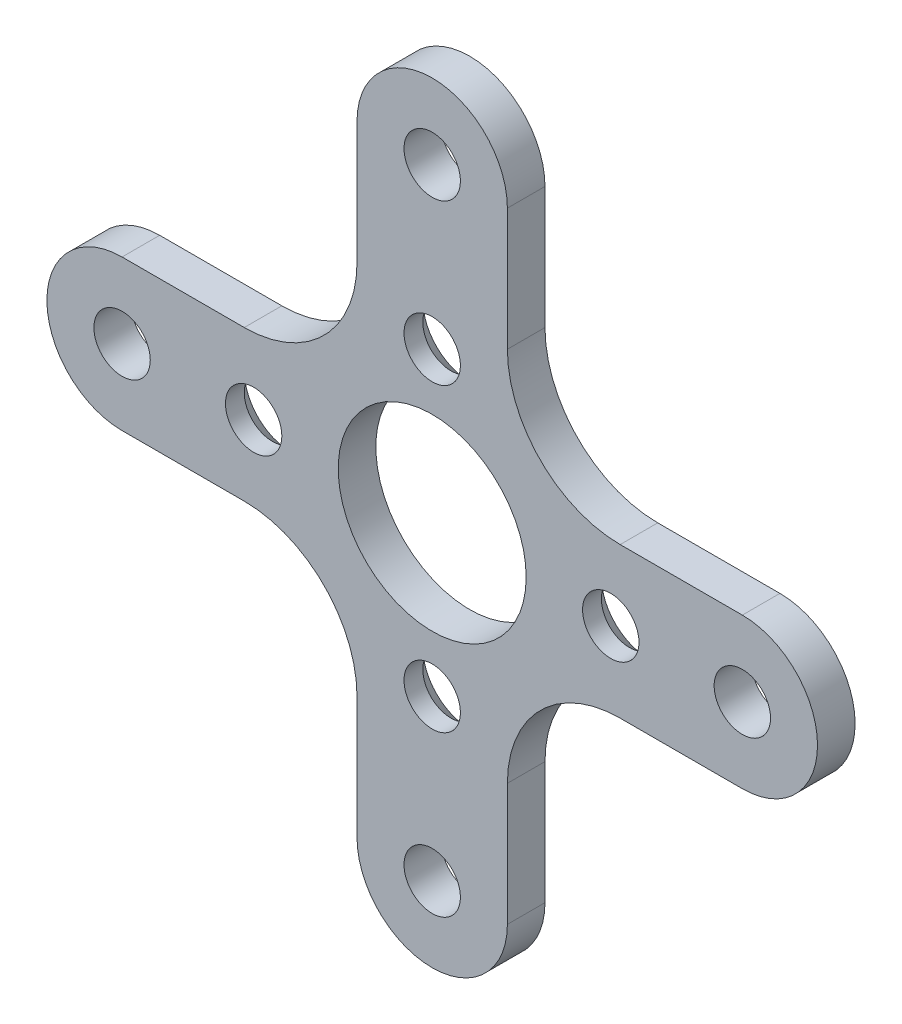
SolidWorks part; units mm, degrees
ref_plane "Ön Düzlem" through (0, 0, 0) normal (0, 0, 1) x (1, 0, 0)
ref_plane "Üst Düzlem" through (0, 0, 0) normal (0, 1, 0) x (1, 0, 0)
ref_plane "Sağ Düzlem" through (0, 0, 0) normal (1, 0, 0) x (0, 0, -1)
sketch "Çizim1" plane through (0, 0, 0) normal (0, 0, 1) x (1, 0, 0)
  line L0 (0, 0) -> (0, 16.5) construction
  line L1 (10, 4) -> (16.5, 4)
  line L2 (10, -4) -> (16.5, -4)
  line L3 (4, -10) -> (4, -16.5)
  line L4 (-4, -10) -> (-4, -16.5)
  line L5 (-10, -4) -> (-16.5, -4)
  line L6 (-10, 4) -> (-16.5, 4)
  line L7 (-4, 10) -> (-4, 16.5)
  line L9 (4, 10) -> (4, 16.5)
  circle A0 centre (0, 8) radius 1.5
  arc A1 (4, 16.5) -> (-4, 16.5) centre (0, 16.5) ccw
  arc A2 (16.5, -4) -> (16.5, 4) centre (16.5, 0) ccw
  circle A3 centre (16.5, 0) radius 1.5
  circle A4 centre (9.5, 0) radius 1.5
  arc A5 (10, -4) -> (4, -10) centre (10, -10) ccw
  arc A6 (4, 10) -> (10, 4) centre (10, 10) ccw
  arc A7 (-4, -16.5) -> (4, -16.5) centre (0, -16.5) ccw
  circle A8 centre (0, 16.5) radius 1.5
  circle A9 centre (0, -16.5) radius 1.5
  circle A10 centre (0, -8) radius 1.5
  arc A11 (-4, -10) -> (-10, -4) centre (-10, -10) ccw
  circle A12 centre (0, 0) radius 5
  arc A13 (-16.5, 4) -> (-16.5, -4) centre (-16.5, 0) ccw
  circle A14 centre (-16.5, 0) radius 1.5
  circle A15 centre (-9.5, 0) radius 1.5
  arc A16 (-10, 4) -> (-4, 10) centre (-10, 10) ccw
  point P2 (0, 0)
  point P6 (-9.5686, 0)
  point P9 (0, 0)
  point P39 (0, 0)
  point P49 (0, 0)
  dimension "D3" = 4
  dimension "D4" = 10
  dimension "D5" = 10
  dimension "D6" = 3
  dimension "D1" = 6
  dimension "D2" = 16.5
  dimension "D7" = 4
  dimension "D8" = 8
  dimension "D9" = 19
extrude "Yükseklik-Ekstrüzyon1" add sketch "Çizim1" along normal blind 2
chamfer "Фаска1" distance 1 angle 45 4 edges at (1.5, -8, 0) (-8, 0, 0) (1.5, 8, 0) (11, 0, 0)
